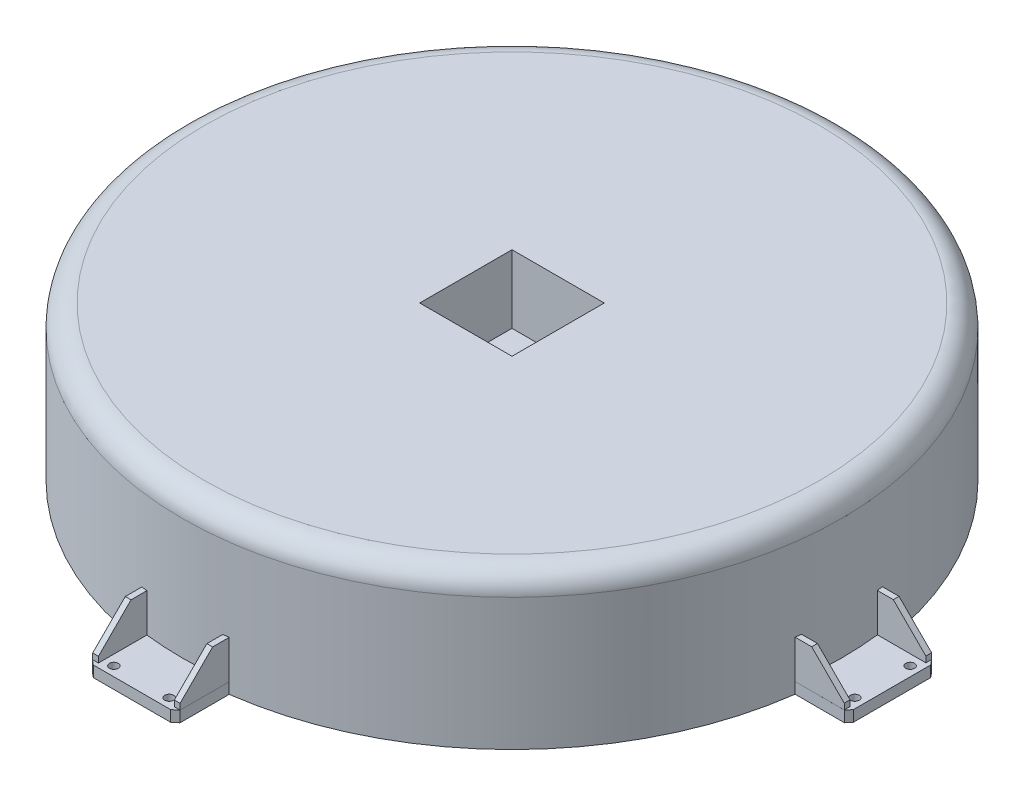
SolidWorks part; units mm, degrees
ref_plane "Ön Düzlem" through (0, 0, 0) normal (0, 0, 1) x (1, 0, 0)
ref_plane "Üst Düzlem" through (0, 0, 0) normal (0, 1, 0) x (1, 0, 0)
ref_plane "Sağ Düzlem" through (0, 0, 0) normal (1, 0, 0) x (0, 0, -1)
sketch "Çizim1" plane through (0, 0, 0) normal (0, 1, 0) x (1, 0, 0)
  circle A0 centre (0, 0) radius 150
  dimension "D1" = 300
extrude "Yükseklik-Ekstrüzyon1" add sketch "Çizim1" along normal blind 70
sketch "Çizim2" plane through (0, 0, 0) normal (0, 1, 0) x (1, 0, 0)
  line L2 (-19.9384, 146.7205) -> (-19.9592, 172.9935)
  line L3 (-19.9592, 172.9935) -> (19.8346, 172.9935)
  line L4 (19.7937, 146.7331) -> (19.8346, 172.9935)
  spline S0 degree 3 poles (-19.9384, 146.7205) (-6.8216, 149.3874) (6.6776, 149.4) (19.7937, 146.7331) knots 0 0 0 0 0.935808 0.935808 0.935808 0.935808
  point P0 (0, 150)
extrude "Yükseklik-Ekstrüzyon14" add sketch "Çizim2" along normal blind 5
sketch "Çizim11" plane through (0, 5, 0) normal (0, 1, 0) x (1, 0, 0)
  line L0 (-19.9577, 171.0614) -> (-17.3412, 171.0614)
  line L2 (-17.3412, 171.0614) -> (-17.3412, 146.6431)
  line L3 (-17.3412, 146.6431) -> (-19.9493, 146.6431)
  line L4 (-19.9493, 146.6431) -> (-19.9577, 171.0614)
  line L5 (-0.0733, 143.3779) -> (-0.0733, 179.3732) construction
  line L6 (17.1946, 146.6431) -> (19.8027, 146.6431)
  line L7 (19.8111, 171.0614) -> (17.1946, 171.0614)
  line L8 (17.1946, 171.0614) -> (17.1946, 146.6431)
  line L9 (19.8027, 146.6431) -> (19.8111, 171.0614)
extrude "Yükseklik-Ekstrüzyon16" add sketch "Çizim11" along normal blind 17.5
sketch "Çizim12" plane through (0, 0, 0) normal (1, 0, 0) x (0, 0, -1)
  line L0 (155.5356, 23.2006) -> (171.3747, 7.3614)
  line L1 (171.3747, 7.3614) -> (171.3747, 23.2006)
  line L2 (171.3747, 23.2006) -> (155.5356, 23.2006)
extrude "Kes-Ekstrüzyon1" cut sketch "Çizim12" against normal blind 27.5 and the other way blind 27.5
sketch "Çizim13" plane through (0, 0, 0) normal (0, 1, 0) x (1, 0, 0)
  line L0 (-19.9577, 171.0614) -> (-17.3412, 173.1968)
  line L1 (-17.3412, 173.1968) -> (-20.1124, 173.1968)
  line L2 (-20.1124, 173.1968) -> (-20.1124, 171.0614)
  line L3 (-20.1124, 171.0614) -> (-19.9577, 171.0614)
  line L4 (0, 147.6673) -> (0, 182.7036) construction
  line L5 (20.1124, 173.1968) -> (20.1124, 171.0614)
  line L6 (17.3412, 173.1968) -> (20.1124, 173.1968)
  line L7 (19.9577, 171.0614) -> (17.3412, 173.1968)
  line L8 (19.9577, 171.0614) -> (20.1124, 171.0614)
extrude "Kes-Ekstrüzyon3" cut sketch "Çizim13" along normal blind 7.5
sketch "Çizim17" plane through (0, 0, 0) normal (0, 1, 0) x (1, 0, 0)
  line L0 (0, 126.077) -> (0, 97.8787) construction
  line L1 (11.7031, 121.8237) -> (9.7031, 121.8234)
  line L2 (9.7031, 121.8234) -> (8.7033, 120.0912)
  line L3 (8.7033, 120.0912) -> (9.7036, 118.3593)
  line L4 (9.7036, 118.3593) -> (11.7036, 118.3596)
  line L5 (11.7036, 118.3596) -> (12.7033, 120.0917)
  line L6 (12.7033, 120.0917) -> (11.7031, 121.8237)
  line L7 (-9.7036, 118.3593) -> (-11.7036, 118.3596)
  line L8 (-11.7036, 118.3596) -> (-12.7033, 120.0917)
  line L9 (-12.7033, 120.0917) -> (-11.7031, 121.8237)
  line L10 (-11.7031, 121.8237) -> (-9.7031, 121.8234)
  line L11 (-9.7031, 121.8234) -> (-8.7033, 120.0912)
  line L12 (-8.7033, 120.0912) -> (-9.7036, 118.3593)
  circle A0 centre (10.7033, 120.0915) radius 1.7321 construction
  dimension "D1" = 2
extrude "Yükseklik-Ekstrüzyon17" add sketch "Çizim17" along normal blind 6
pattern_circular "Dairesel Kaplama1" count 4 over 360 about axis through (0, 0, 0) along (0, 1, 0) of "Yükseklik-Ekstrüzyon16", "Yükseklik-Ekstrüzyon14", "Yükseklik-Ekstrüzyon17", "Kes-Ekstrüzyon3"
pattern_circular "Dairesel Kaplama2" count 4 over 360 about axis through (0, 0, 0) along (0, 1, 0) of "Kes-Ekstrüzyon1"
fillet "Radyus1" radius 10 1 edges at (0, 70, 150)
sketch "Çizim18" plane through (0, 70, 0) normal (0, 1, 0) x (1, 0, 0)
  line L1 (-21, -21) -> (21, -21)
  line L2 (-21, -21) -> (-21, 21)
  line L3 (-21, 21) -> (21, 21)
  line L4 (21, -21) -> (21, 21)
  line L5 (-21, -21) -> (21, 21) construction
  line L6 (-21, 21) -> (21, -21) construction
  point P0 (0, 0)
  dimension "D1" = 42
  dimension "D2" = 42
sketch "Çizim19" plane through (0, 5, 0) normal (0, 1, 0) x (1, 0, 0)
  line L0 (0, 178.6514) -> (0, 132.2003) construction
  circle A0 centre (-12.5902, 168.659) radius 2
  circle A1 centre (12.5902, 168.659) radius 2
  circle A2 centre (168.659, 12.5902) radius 2
  circle A3 centre (168.659, -12.5902) radius 2
  circle A4 centre (12.5902, -168.659) radius 2
  circle A5 centre (-12.5902, -168.659) radius 2
  circle A6 centre (-168.659, -12.5902) radius 2
  circle A7 centre (-168.659, 12.5902) radius 2
  point P22 (0, 0)
  dimension "D1" = 4
  dimension "D2" = 4
extrude "Kes-Ekstrüzyon5" cut sketch "Çizim19" against normal blind 10
ref_plane "Düzlem1" through (0, 70, 0) normal (0, 1, 0) x (1, 0, 0)
sketch "Çizim22" plane through (0, 70, 0) normal (0, 1, 0) x (1, 0, 0)
  circle A0 centre (0, 0) radius 140
extrude "Yükseklik-Ekstrüzyon18" add sketch "Çizim22" against normal blind 1
extrude "Kes-Ekstrüzyon8" cut sketch "Çizim18" against normal blind 31 and the other way blind 11
